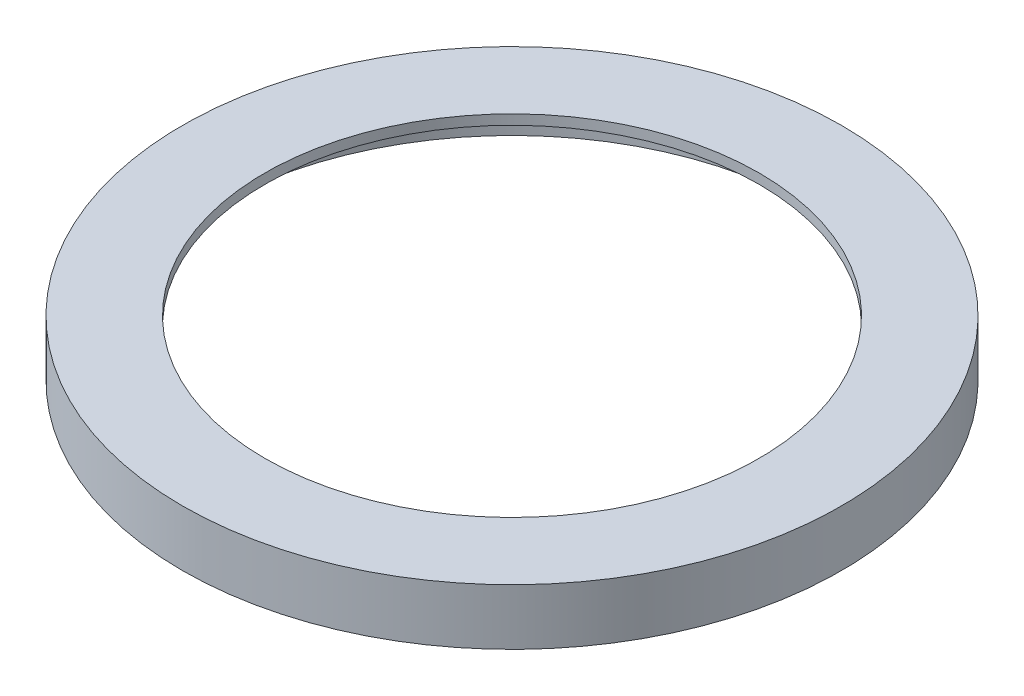
SolidWorks part; units mm, degrees
ref_plane "Спереди" through (0, 0, 0) normal (0, 0, 1) x (1, 0, 0)
ref_plane "Сверху" through (0, 0, 0) normal (0, 1, 0) x (1, 0, 0)
ref_plane "Справа" through (0, 0, 0) normal (1, 0, 0) x (0, 0, -1)
sketch "Эскиз1" plane through (0, 0, 0) normal (0, 1, 0) x (1, 0, 0)
  circle A0 centre (0, -3.1032) radius 100
  circle A1 centre (0, -3.1032) radius 75
extrude "Вытянуть1" add sketch "Эскиз1" along normal blind 17 from offset 1
sketch "Эскиз5" plane through (0, -1, 0) normal (0, -1, 0) x (1, 0, 0)
  circle A0 centre (0, 3.1032) radius 91
extrude "Вырез-Вытянуть1" cut sketch "Эскиз5" against normal blind 14
